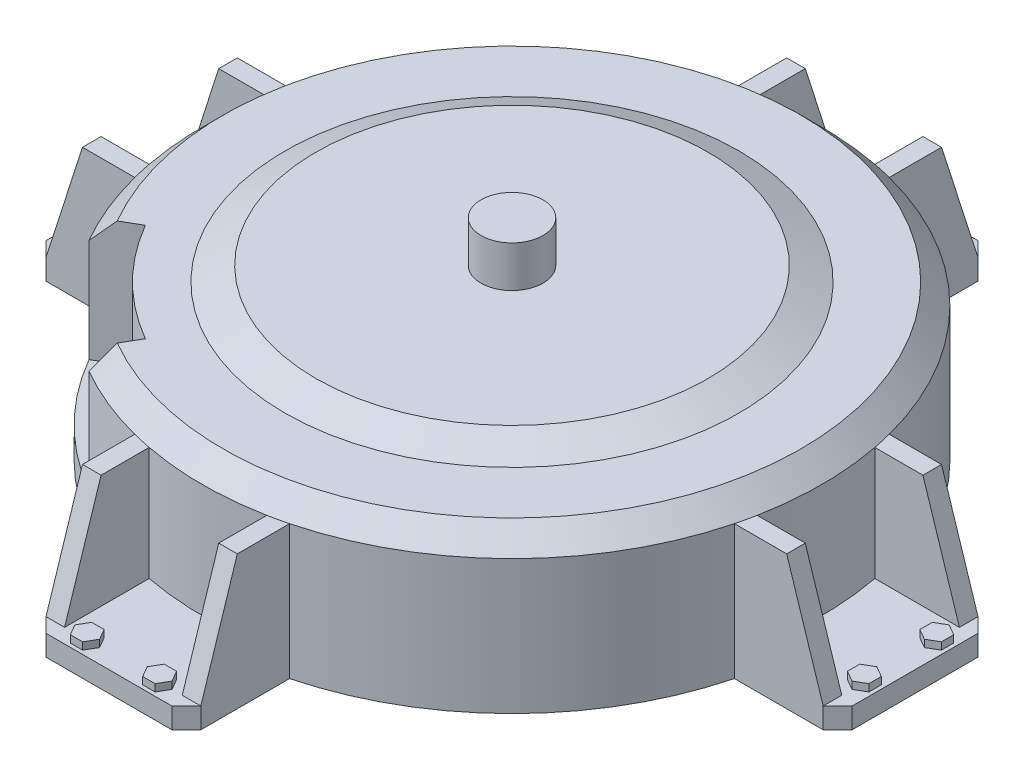
SolidWorks part; units mm, degrees
material "Gray Cast Iron"
ref_plane "Front" through (0, 0, 0) normal (0, 0, 1) x (1, 0, 0)
ref_plane "Top" through (0, 0, 0) normal (0, 1, 0) x (1, 0, 0)
ref_plane "Right" through (0, 0, 0) normal (1, 0, 0) x (0, 0, -1)
sketch "Sketch1" plane through (0, 0, 0) normal (0, 1, 0) x (1, 0, 0)
  circle A0 centre (0, 0) radius 150
  dimension "D1" = 300
extrude "Boss-Extrude1" add sketch "Sketch1" along normal blind 75
chamfer "Chamfer1" distance 10 angle 45 1 edges at (0, 75, 150)
ref_plane "Plane1" through (0, 0, 0) normal (0, -1, 0) x (-1, 0, 0)
sketch "Sketch2" plane through (0, 0, 0) normal (0, -1, 0) x (-1, 0, 0)
  line L1 (145.2369, 37.5) -> (195.2369, 37.5)
  line L3 (145.2369, -37.5) -> (195.2369, -37.5)
  line L4 (195.2369, 37.5) -> (195.2369, -37.5)
  line L5 (150, 0) -> (195.2369, -37.5) construction
  line L6 (150, 0) -> (195.2369, 37.5) construction
  circle A0 centre (0, 0) radius 150 construction
  arc A1 (145.2369, -37.5) -> (145.2369, 37.5) centre (0, 0) ccw
  point P0 (150, 0)
  dimension "D1" = 75
  dimension "D2" = 50
extrude "Boss-Extrude2" add sketch "Sketch2" against normal blind 10 contours L1 L4 L3 A1
chamfer "Chamfer2" distance 7 angle 45 2 edges at (-195.2369, 5, -37.5) (-195.2369, 5, 37.5)
sketch "Sketch3" plane through (0, 0, 37.5) normal (0, 0, 1) x (1, 0, 0)
  line L0 (-145.2369, 10) -> (-145.2369, 65)
  line L1 (-150, 65) -> (150, 65) construction
  line L2 (-145.2369, 65) -> (-170.5569, 65)
  line L3 (-170.5569, 65) -> (-188.2369, 10)
  line L4 (-188.2369, 10) -> (-145.2369, 10)
  dimension "D1" = 17.68
extrude "Boss-Extrude3" add sketch "Sketch3" against normal blind 9 contours L2 L3 L4 L0
sketch "Sketch4" plane through (0, 10, 0) normal (0, 1, 0) x (1, 0, 0)
  line L0 (-188.2369, 37.5) -> (-188.2369, -37.5) construction
  line L2 (-188.2369, -23.54) -> (-183.0407, -20.54)
  line L3 (-183.0407, -20.54) -> (-183.0407, -14.54)
  line L4 (-183.0407, -14.54) -> (-188.2369, -11.54)
  line L5 (-188.2369, -11.54) -> (-193.433, -14.54)
  line L6 (-193.433, -14.54) -> (-193.433, -20.54)
  line L7 (-193.433, -20.54) -> (-188.2369, -23.54)
  circle A0 centre (-188.2369, -17.54) radius 5.1962 construction
  dimension "D1" = 6
  dimension "D2" = 4.96
extrude "Boss-Extrude4" add sketch "Sketch4" along normal blind 3.5 contours L5 L6 L7 L2 L3 L4
ref_plane "Plane2" through (0, 0, 0) normal (0, 0, 1) x (1, 0, 0)
mirror "Mirror1" about plane through (0, 0, 0) normal (0, 0, 1) of "Boss-Extrude3", "Boss-Extrude4"
pattern_circular "CirPattern1" count 4 over 360 about axis through (0, 0, 0) along (0, 1, 0) of "Boss-Extrude2", "Chamfer2", "Boss-Extrude3", "Boss-Extrude4", "Mirror1"
sketch "Sketch6" plane through (0, 75, 0) normal (0, 1, 0) x (1, 0, 0)
  line L0 (-245.3604, 0) -> (0, 0) construction
  line L1 (0, 0) -> (0, -231.205) construction
  line L2 (-112.5833, -65) -> (-129.9038, -75)
  line L3 (-65, -112.5833) -> (-75, -129.9038)
  arc A0 (-145.2369, -37.5) -> (-37.5, -145.2369) centre (0, 0) ccw construction
  arc A1 (-129.9038, -75) -> (-75, -129.9038) centre (0, 0) ccw
  arc A2 (-112.5833, -65) -> (-65, -112.5833) centre (0, 0) ccw
  dimension "D3" = 260
  dimension "D1" = 30
  dimension "D2" = 30
  dimension "D4" = 65
  dimension "D5" = 112.5833
extrude "Cut-Extrude1" cut sketch "Sketch6" against normal blind 60
sketch "Sketch7" plane through (0, 75, 0) normal (0, 1, 0) x (1, 0, 0)
  circle A0 centre (0, 0) radius 110
  dimension "D1" = 220
ref_plane "Plane3" through (0, 82, 0) normal (0, 1, 0) x (1, 0, 0)
sketch "Sketch8" plane through (0, 82, 0) normal (0, 1, 0) x (1, 0, 0)
  circle A3 centre (0, 0) radius 95
  circle A4 centre (0, 0) radius 95
  dimension "D1" = 15
loft "Loft1" add profiles "Sketch7", "Sketch8"
sketch "Sketch9" plane through (0, 82, 0) normal (0, 1, 0) x (1, 0, 0)
  circle A0 centre (0, 0) radius 15
  dimension "D1" = 30
extrude "Boss-Extrude5" add sketch "Sketch9" along normal blind 20 contours A0
